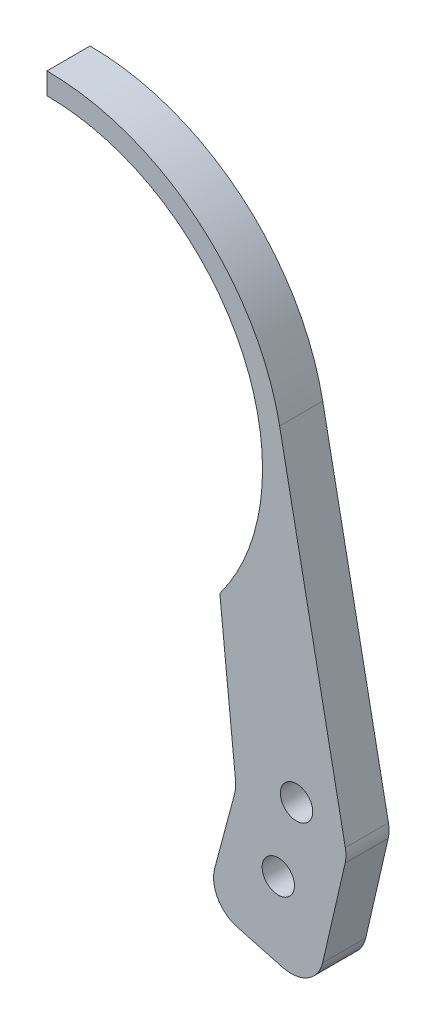
SolidWorks part; units mm, degrees
ref_plane "前视基准面" through (0, 0, 0) normal (0, 0, 1) x (1, 0, 0)
ref_plane "上视基准面" through (0, 0, 0) normal (0, 1, 0) x (1, 0, 0)
ref_plane "右视基准面" through (0, 0, 0) normal (1, 0, 0) x (0, 0, -1)
other "Configuration Table"
sketch "草图1" plane through (0, 0, 0) normal (0, 0, 1) x (1, 0, 0)
  line L1 (-10.9406, 59.049) -> (-10.9406, 83.1005) construction
  line L2 (-10.9406, 79.049) -> (-10.9406, 81.049)
  line L3 (10.6416, 63.3162) -> (16.8623, 31.8535)
  line L4 (16.8623, 31.8535) -> (13.9358, 19.1535)
  line L6 (13.9358, 19.1535) -> (3.839, 21.8588)
  line L8 (3.839, 21.8588) -> (6.6125, 32.2104)
  line L9 (4.5298, 24.4373) -> (7.1411, 34.1833) construction
  line L10 (6.6125, 32.2104) -> (5.0957, 47.0976)
  arc A0 (5.0957, 47.0976) -> (-10.9406, 79.049) centre (-10.9406, 59.049) ccw
  arc A6 (10.6416, 63.3162) -> (-10.9406, 81.049) centre (-10.9406, 59.049) ccw
  arc A7 (16.843, 31.7662) -> (7.1411, 34.1833) centre (11.9707, 32.8892) ccw construction
  circle A8 centre (10.5203, 27.0672) radius 1.5
  circle A9 centre (12.2124, 33.8596) radius 1.5
  point P1 (5.0957, 47.0976)
  dimension "D2" = 44
  dimension "D3" = 40
extrude "凸台-拉伸1" add sketch "草图1" along normal blind 4
fillet "圆角1" radius 3 4 edges at (6.6125, 32.2104, 2) (3.839, 21.8588, 2) (13.9358, 19.1535, 2) (16.8623, 31.8535, 2)
